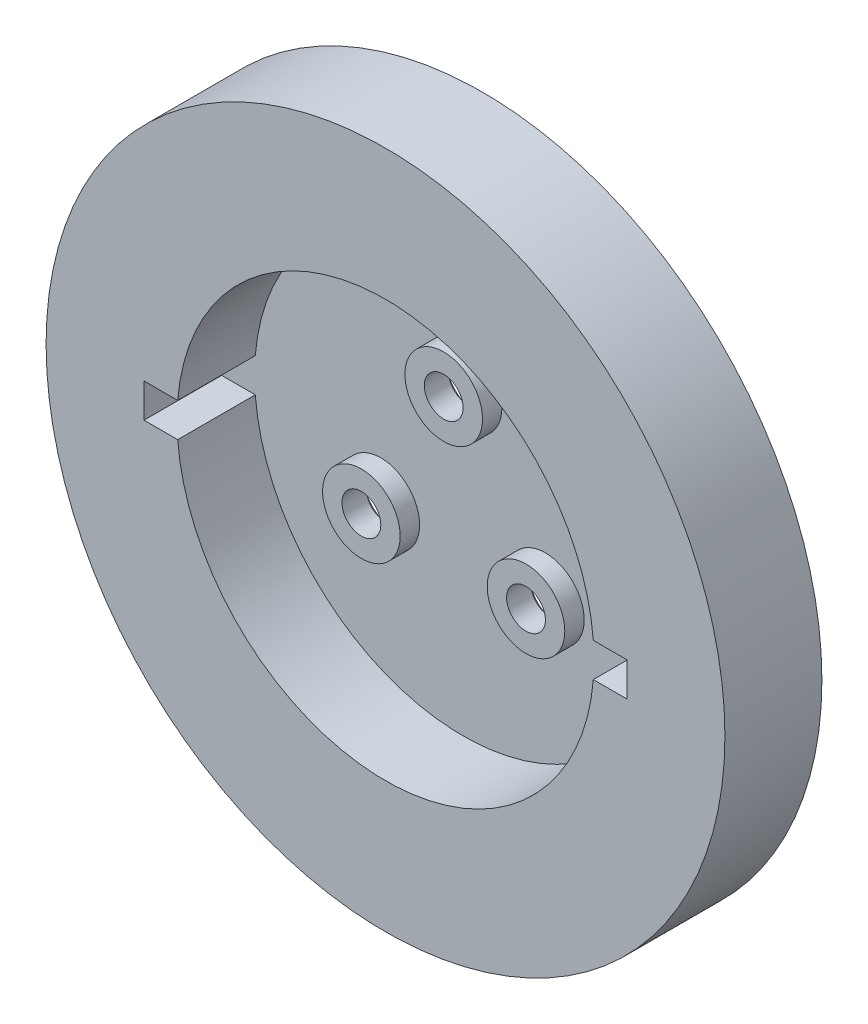
SolidWorks part; units mm, degrees
ref_plane "前视基准面" through (0, 0, 0) normal (0, 0, 1) x (1, 0, 0)
ref_plane "上视基准面" through (0, 0, 0) normal (0, 1, 0) x (1, 0, 0)
ref_plane "右视基准面" through (0, 0, 0) normal (1, 0, 0) x (0, 0, -1)
other "Configuration Table"
sketch "草图1" plane through (0, 0, 0) normal (0, 0, 1) x (1, 0, 0)
  line L0 (0, 0) -> (0, 9.8)
  line L1 (0, 0) -> (-8.487, -4.9)
  line L2 (0, 0) -> (8.487, -4.9)
  circle A0 centre (0, 0) radius 35
  dimension "D1" = 70
  dimension "D2" = 9.8
  dimension "D3" = 120
  dimension "D4" = 9.8
  dimension "D5" = 9.8
  dimension "D6" = 120
extrude "凸台-拉伸1" add sketch "草图1" along normal blind 10
sketch "草图2" plane through (0, 0, 10) normal (0, 0, 1) x (1, 0, 0)
  line L0 (0, 0) -> (24.9, 0) construction
  line L1 (24.9, 0) -> (24.9, 1.75)
  line L2 (24.9, 0) -> (24.9, -1.75)
  line L3 (24.9, 1.75) -> (21.4287, 1.75)
  line L4 (24.9, -1.75) -> (21.4287, -1.75)
  line L5 (-24.9, -1.75) -> (-21.4287, -1.75)
  line L6 (-24.9, 0) -> (-24.9, -1.75)
  line L7 (-24.9, 0) -> (-24.9, 1.75)
  line L8 (-24.9, 1.75) -> (-21.4287, 1.75)
  circle A0 centre (0, 0) radius 21.5
  circle A1 centre (0, 0) radius 17.5
  point P16 (0, 0)
  dimension "D1" = 2
extrude "切除-拉伸1" cut sketch "草图2" against normal blind 8
sketch "草图4" plane through (0, 0, 0) normal (0, 0, -1) x (-1, 0, 0)
  line L0 (0, 0) -> (0, 9.8)
  line L1 (0, 0) -> (8.487, -4.9)
  line L2 (0, 0) -> (-8.487, -4.9)
  circle A0 centre (8.487, -4.9) radius 4
  circle A1 centre (-8.487, -4.9) radius 4
  circle A2 centre (0, 9.8) radius 4
  point P7 (0, 0)
  point P13 (0, 0)
  dimension "D2" = 8
  dimension "D1" = 3
  dimension "D3" = 3
extrude "切除-拉伸2" cut sketch "草图4" against normal blind 1.5
sketch "草图6" plane through (0, 0, 1.5) normal (0, 0, -1) x (-1, 0, 0)
  line L0 (0, 0) -> (0, 9.8)
  circle A0 centre (0, 9.8) radius 2
  circle A1 centre (8.487, -4.9) radius 2
  circle A2 centre (-8.487, -4.9) radius 2
  point P11 (0, 0)
  dimension "D1" = 3
extrude "切除-拉伸3" cut sketch "草图6" against normal through all
sketch "草图7" plane through (0, 0, 2) normal (0, 0, 1) x (1, 0, 0)
  circle A0 centre (0, 9.8) radius 4
  circle A1 centre (0, 9.8) radius 2
  dimension "D1" = 8
extrude "凸台-拉伸2" add sketch "草图7" along normal blind 2
sketch "草图8" plane through (0, 0, 2) normal (0, 0, 1) x (1, 0, 0)
  circle A0 centre (-8.487, -4.9) radius 2
  circle A1 centre (-8.487, -4.9) radius 4
  dimension "D1" = 8
extrude "凸台-拉伸3" add sketch "草图8" along normal blind 2
sketch "草图9" plane through (0, 0, 2) normal (0, 0, 1) x (1, 0, 0)
  circle A0 centre (8.487, -4.9) radius 2
  circle A1 centre (8.487, -4.9) radius 4
  dimension "D1" = 8
extrude "凸台-拉伸4" add sketch "草图9" along normal blind 2
